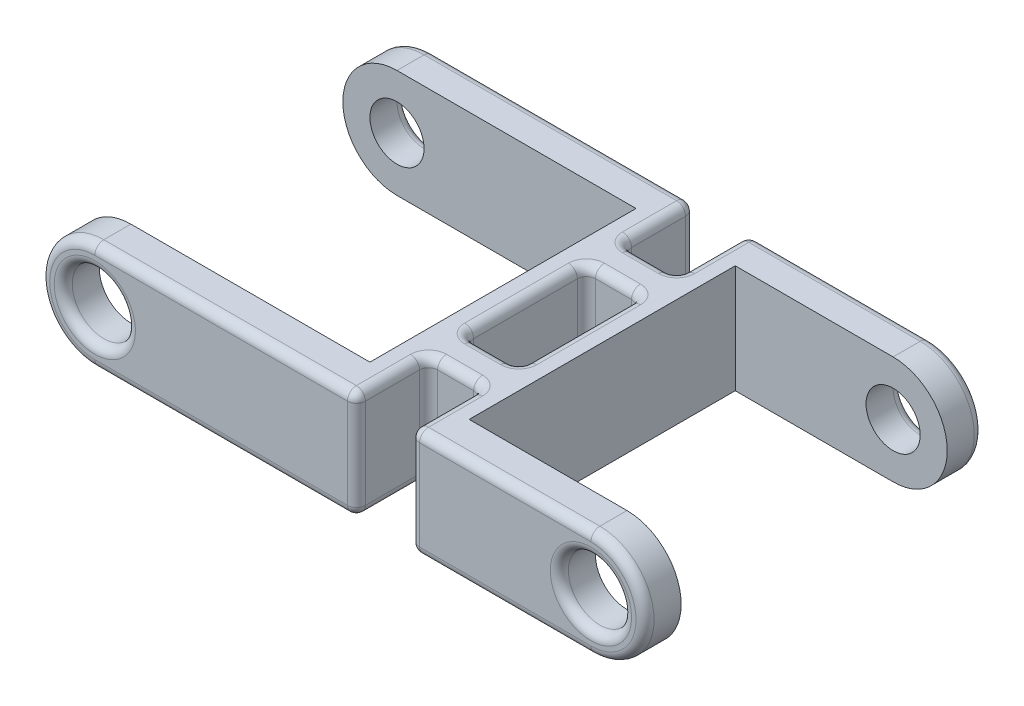
SolidWorks part; units mm, degrees
ref_plane "Front Plane" through (0, 0, 0) normal (0, 0, 1) x (1, 0, 0)
ref_plane "Top Plane" through (0, 0, 0) normal (0, 1, 0) x (1, 0, 0)
ref_plane "Right Plane" through (0, 0, 0) normal (1, 0, 0) x (0, 0, -1)
sketch "Sketch1" plane through (0, 0, 0) normal (1, 0, 0) x (0, 0, -1)
  line L1 (-19.8617, 7.337) -> (17.6383, 7.337)
  line L2 (-19.8617, 7.337) -> (-19.8617, -4.663)
  line L3 (-19.8617, -4.663) -> (17.6383, -4.663)
  line L4 (17.6383, 7.337) -> (17.6383, -4.663)
  dimension "D1" = 37.5
  dimension "D2" = 12
extrude "Boss-Extrude1" add sketch "Sketch1" along normal blind 2.5
sketch "Sketch3" plane through (0, 0, -17.6383) normal (0, 0, -1) x (-1, 0, 0)
  line L1 (0, 7.337) -> (26.5, 7.337)
  line L2 (0, 7.337) -> (0, -4.663)
  line L3 (0, -4.663) -> (26.5, -4.663)
  arc A0 (26.5, -4.663) -> (26.5, 7.337) centre (26.5, 1.337) ccw
  circle A1 centre (26.5, 1.337) radius 3
  dimension "D2" = 6
  dimension "D1" = 26.5
extrude "Boss-Extrude2" add sketch "Sketch3" against normal blind 4
sketch "Sketch4" plane through (0, 0, 19.8617) normal (0, 0, 1) x (1, 0, 0)
  line L1 (0, 7.337) -> (-26.5, 7.337)
  line L2 (0, 7.337) -> (0, -4.663)
  line L3 (0, -4.663) -> (-26.5, -4.663)
  arc A0 (-26.5, 7.337) -> (-26.5, -4.663) centre (-26.5, 1.337) ccw
  circle A1 centre (-26.5, 1.337) radius 3.5
  dimension "D1" = 7
extrude "Boss-Extrude3" add sketch "Sketch4" against normal blind 4
sketch "Sketch5" plane through (2.5, 0, 0) normal (1, 0, 0) x (0, 0, -1)
  line L0 (17.6383, 7.337) -> (-19.8617, 7.337) construction
  line L1 (-11.8617, 7.337) -> (-7.8617, 7.337)
  line L2 (-11.8617, 7.337) -> (-11.8617, -4.663)
  line L3 (-11.8617, -4.663) -> (-7.8617, -4.663)
  line L4 (9.6383, 7.337) -> (9.6383, -4.663)
  line L5 (-19.8617, -4.663) -> (17.6383, -4.663) construction
  line L6 (-19.8617, 7.337) -> (-19.8617, -4.663) construction
  line L7 (17.6383, -4.663) -> (17.6383, 7.337) construction
  line L8 (5.6383, 7.337) -> (9.6383, 7.337)
  line L10 (-7.8617, 7.337) -> (-7.8617, -4.663)
  line L12 (5.6383, 7.337) -> (5.6383, -4.663)
  line L13 (5.6383, -4.663) -> (9.6383, -4.663)
  dimension "D1" = 8
  dimension "D2" = 8
  dimension "D3" = 4
  dimension "D4" = 4
extrude "Boss-Extrude4" add sketch "Sketch5" along normal blind 6
sketch "Sketch6" plane through (8.5, 0, 0) normal (1, 0, 0) x (0, 0, -1)
  line L1 (-19.8617, 7.337) -> (17.6383, 7.337)
  line L2 (-19.8617, 7.337) -> (-19.8617, -4.663)
  line L3 (-19.8617, -4.663) -> (17.6383, -4.663)
  line L4 (17.6383, 7.337) -> (17.6383, -4.663)
extrude "Boss-Extrude5" add sketch "Sketch6" along normal blind 2.5
sketch "Sketch8" plane through (0, 0, 19.8617) normal (0, 0, 1) x (1, 0, 0)
  line L1 (11, 7.337) -> (28.5, 7.337)
  line L2 (11, 7.337) -> (11, -4.663)
  line L3 (11, -4.663) -> (28.5, -4.663)
  arc A0 (28.5, -4.663) -> (28.5, 7.337) centre (28.5, 1.337) ccw
  circle A1 centre (28.5, 1.337) radius 3.5
  dimension "D2" = 7
  dimension "D1" = 17.5
extrude "Boss-Extrude6" add sketch "Sketch8" against normal blind 4
sketch "Sketch9" plane through (0, 0, -17.6383) normal (0, 0, -1) x (-1, 0, 0)
  line L1 (-11, 7.337) -> (-28.5, 7.337)
  line L2 (-11, 7.337) -> (-11, -4.663)
  line L3 (-11, -4.663) -> (-28.5, -4.663)
  arc A0 (-28.5, 7.337) -> (-28.5, -4.663) centre (-28.5, 1.337) ccw
  circle A1 centre (-28.5, 1.337) radius 3
  dimension "D1" = 6
extrude "Boss-Extrude7" add sketch "Sketch9" against normal blind 4
fillet "Fillet1" radius 1 48 edges at (5.5, -4.663, 7.8617) (5.5, 7.337, 7.8617) (5.5, 7.337, -5.6383) (5.5, -4.663, -5.6383) (8.5, 1.337, -5.6383) (8.5, 7.337, 1.1117) (8.5, 1.337, 7.8617) (8.5, -4.663, 1.1117) (2.5, 1.337, 7.8617) (2.5, 7.337, 1.1117) (2.5, 1.337, -5.6383) (2.5, -4.663, 1.1117) (2.5, -4.663, -13.6383) (2.5, 7.337, -13.6383) (-26.5, 4.337, -17.6383) (2.5, 1.337, -17.6383) (-12, 7.337, -17.6383) (-32.5, 1.337, -17.6383) (-12, -4.663, -17.6383) (5.5, -4.663, -9.6383) (5.5, 7.337, -9.6383) (2.5, 1.337, -9.6383) (8.5, 7.337, -13.6383) (8.5, 1.337, -9.6383) (8.5, -4.663, -13.6383) (25.5, 1.337, -17.6383) (18.5, -4.663, -17.6383) (34.5, 1.337, -17.6383) (18.5, 7.337, -17.6383) (8.5, 1.337, -17.6383) (2.5, -4.663, 15.8617) (2.5, 7.337, 15.8617) (-23, 1.337, 19.8617) (2.5, 1.337, 19.8617) (-12, -4.663, 19.8617) (-32.5, 1.337, 19.8617) (-12, 7.337, 19.8617) (5.5, 7.337, 11.8617) (5.5, -4.663, 11.8617) (2.5, 1.337, 11.8617) (8.5, -4.663, 15.8617) (8.5, 1.337, 11.8617) (8.5, 7.337, 15.8617) (32, 1.337, 19.8617) (18.5, 7.337, 19.8617) (34.5, 1.337, 19.8617) (18.5, -4.663, 19.8617) (8.5, 1.337, 19.8617)
